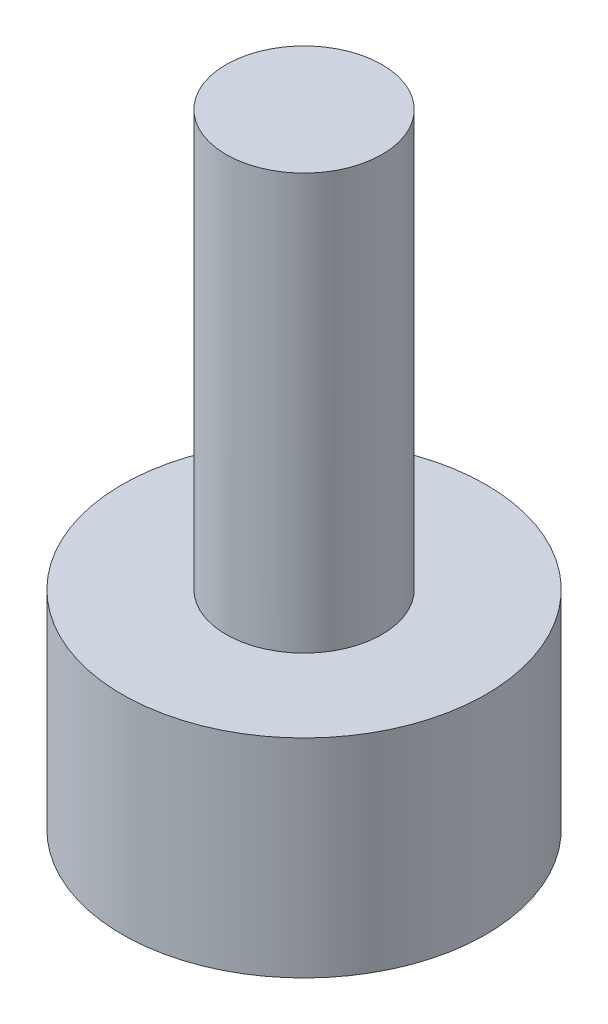
SolidWorks part; units mm, degrees
material "AISI 304"
ref_plane "前视基准面" through (0, 0, 0) normal (0, 0, 1) x (1, 0, 0)
ref_plane "上视基准面" through (0, 0, 0) normal (0, 1, 0) x (1, 0, 0)
ref_plane "右视基准面" through (0, 0, 0) normal (1, 0, 0) x (0, 0, -1)
other "Configuration Table"
sketch "草图1" plane through (0, 0, 0) normal (0, 1, 0) x (1, 0, 0)
  circle A0 centre (0, 0) radius 6
  dimension "D1" = 12
extrude "凸台-拉伸1" add sketch "草图1" along normal blind 32
sketch "草图3" plane through (0, 0, 0) normal (0, -1, 0) x (1, 0, 0)
  circle A0 centre (0, 0) radius 14
  circle A1 centre (0, 0) radius 2.5
  dimension "D1" = 28
  dimension "D2" = 5
extrude "凸台-拉伸2" add sketch "草图3" along normal blind 16
